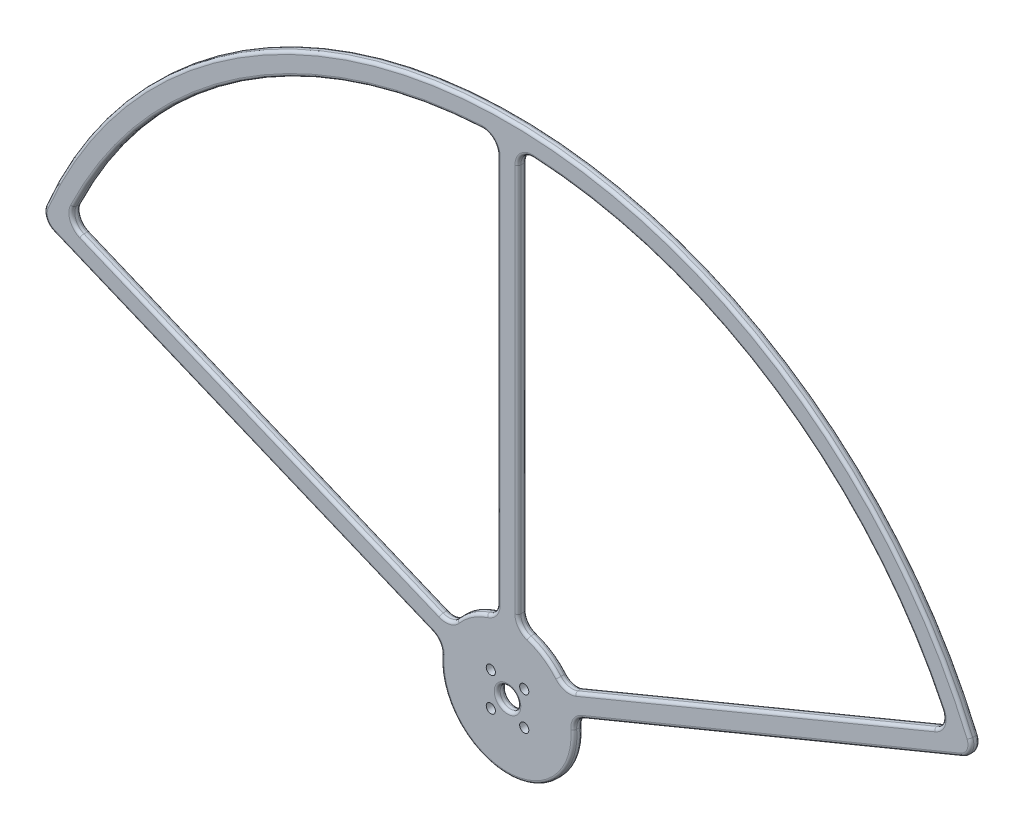
SolidWorks part; units mm, degrees
ref_plane "정면" through (0, 0, 0) normal (0, 0, 1) x (1, 0, 0)
ref_plane "윗면" through (0, 0, 0) normal (0, 1, 0) x (1, 0, 0)
ref_plane "우측면" through (0, 0, 0) normal (1, 0, 0) x (0, 0, -1)
sketch "스케치1" plane through (0, 0, 0) normal (0, 0, 1) x (1, 0, 0)
  line L0 (153.8017, 59.8323) -> (25.502, 6.7749)
  line L3 (-3.5, 26.1534) -> (-3.5, 157.7712)
  line L6 (3.5, 26.1534) -> (3.5, 157.7712)
  line L9 (22.8232, 13.242) -> (144.4222, 63.61)
  line L15 (-22.8232, 13.242) -> (-144.4222, 63.61)
  line L18 (-25.502, 6.7749) -> (-153.5265, 59.8044)
  line L21 (-153.6251, 59.844) -> (-153.676, 59.8638)
  circle A0 centre (0, 0) radius 3.5
  arc A1 (-22.4308, 1.7636) -> (22.4308, 1.7636) centre (0, 0) ccw
  arc A2 (156.4936, 66.4059) -> (-156.463, 66.4781) centre (0, 0) ccw
  arc A5 (-6.9545, 21.3982) -> (-17.108, 14.6139) centre (0, 0) ccw
  arc A6 (-8.769, 162.764) -> (-147.0185, 70.3886) centre (0, 0) ccw
  arc A7 (17.108, 14.6139) -> (6.9545, 21.3982) centre (0, 0) ccw
  arc A8 (147.0185, 70.3886) -> (8.769, 162.764) centre (0, 0) ccw
  arc A9 (-153.6251, 59.844) -> (-153.5265, 59.8044) centre (-155.44, 55.185) cw
  arc A10 (-153.676, 59.8638) -> (-156.463, 66.4781) centre (-151.8611, 64.5228) cw
  arc A11 (-3.5, 157.7712) -> (-8.769, 162.764) centre (-8.5, 157.7712) ccw
  arc A12 (3.5, 157.7712) -> (8.769, 162.764) centre (8.5, 157.7712) cw
  arc A13 (144.4222, 63.61) -> (147.0185, 70.3886) centre (142.5088, 68.2294) ccw
  arc A14 (-17.108, 14.6139) -> (-22.8232, 13.242) centre (-20.9098, 17.8614) cw
  arc A15 (-3.5, 26.1534) -> (-6.9545, 21.3982) centre (-8.5, 26.1534) cw
  arc A16 (3.5, 26.1534) -> (6.9545, 21.3982) centre (8.5, 26.1534) ccw
  arc A17 (22.8232, 13.242) -> (17.108, 14.6139) centre (20.9098, 17.8614) cw
  arc A18 (25.502, 6.7749) -> (22.4308, 1.7636) centre (27.4154, 2.1555) ccw
  arc A19 (-22.4308, 1.7636) -> (-25.502, 6.7749) centre (-27.4154, 2.1555) ccw
  arc A20 (-147.0185, 70.3886) -> (-144.4222, 63.61) centre (-142.5088, 68.2294) ccw
  arc A21 (153.8017, 59.8323) -> (156.4936, 66.4059) centre (151.8909, 64.4528) ccw
  point P10 (0, 86.75)
  point P11 (80.1465, 33.1978)
  point P12 (-78.5298, 32.5281)
  point P37 (-3.5, 22.2261)
  point P42 (19.1949, 11.7391)
  dimension "D1" = 45
  dimension "D2" = 7
  dimension "D3" = 340
  dimension "D4" = 5
  dimension "D5" = 5
extrude "보스-돌출1" add sketch "스케치1" along normal blind 3
fillet "필렛1" radius 1 54 edges at (4.4548, 23.2146, 3) (3.5, 91.9623, 3) (5.0609, 161.4006, 3) (90.5579, 135.5295, 3) (147.178, 66.441, 3) (83.6227, 38.426, 3) (19.7427, 12.9996, 3) (-23.1523, 4.7682, 3) (-89.5143, 33.2896, 3) (-153.5757, 59.8245, 3) (-153.6505, 59.8539, 3) (-156.4688, 62.5813, 3) (0.0392, 170, 3) (156.5179, 62.5579, 3) (89.6518, 33.3036, 3) (23.1523, 4.7682, 3) (-19.7427, 12.9996, 3) (-83.6227, 38.426, 3) (-147.178, 66.441, 3) (-90.5579, 135.5295, 3) (-5.0609, 161.4006, 3) (-3.5, 91.9623, 3) (-4.4548, 23.2146, 3) (-4.4548, 23.2146, 0) (-12.5003, 18.7081, 0) (-19.7427, 12.9996, 0) (-83.6227, 38.426, 0) (-147.178, 66.441, 0) (-90.5579, 135.5295, 0) (-5.0609, 161.4006, 0) (5.0609, 161.4006, 0) (90.5579, 135.5295, 0) (147.178, 66.441, 0) (83.6227, 38.426, 0) (19.7427, 12.9996, 0) (4.4548, 23.2146, 0) (23.1523, 4.7682, 0) (0, -22.5, 0) (-23.1523, 4.7682, 0) (-89.5143, 33.2896, 0) (-153.5757, 59.8245, 0) (-153.6505, 59.8539, 0) (-156.4688, 62.5813, 0) (0.0392, 170, 0) (156.5179, 62.5579, 0) (12.5003, 18.7081, 3) (12.5003, 18.7081, 0) (0, -22.5, 3) (-12.5003, 18.7081, 3) (3.5, 0, 3) (3.5, 0, 0) (-3.5, 91.9623, 0) (3.5, 91.9623, 0) (89.6518, 33.3036, 0)
sketch "스케치3" plane through (0, 0, 0) normal (0, 0, -1) x (-1, 0, 0)
  line L5 (-5.6569, 5.6569) -> (5.6569, -5.6569) construction
  line L6 (-5.6569, -5.6569) -> (5.6569, 5.6569) construction
  circle A1 centre (-5.6569, 5.6569) radius 1.55
  circle A2 centre (5.6569, 5.6569) radius 1.55
  circle A3 centre (5.6569, -5.6569) radius 1.55
  circle A4 centre (-5.6569, -5.6569) radius 1.55
  point P3 (5.6567, -5.657)
  dimension "D2" = 3.1
  dimension "D3" = 3.1
  dimension "D4" = 3.1
  dimension "D5" = 3.1
extrude "컷-돌출1" cut sketch "스케치3" against normal blind 3
